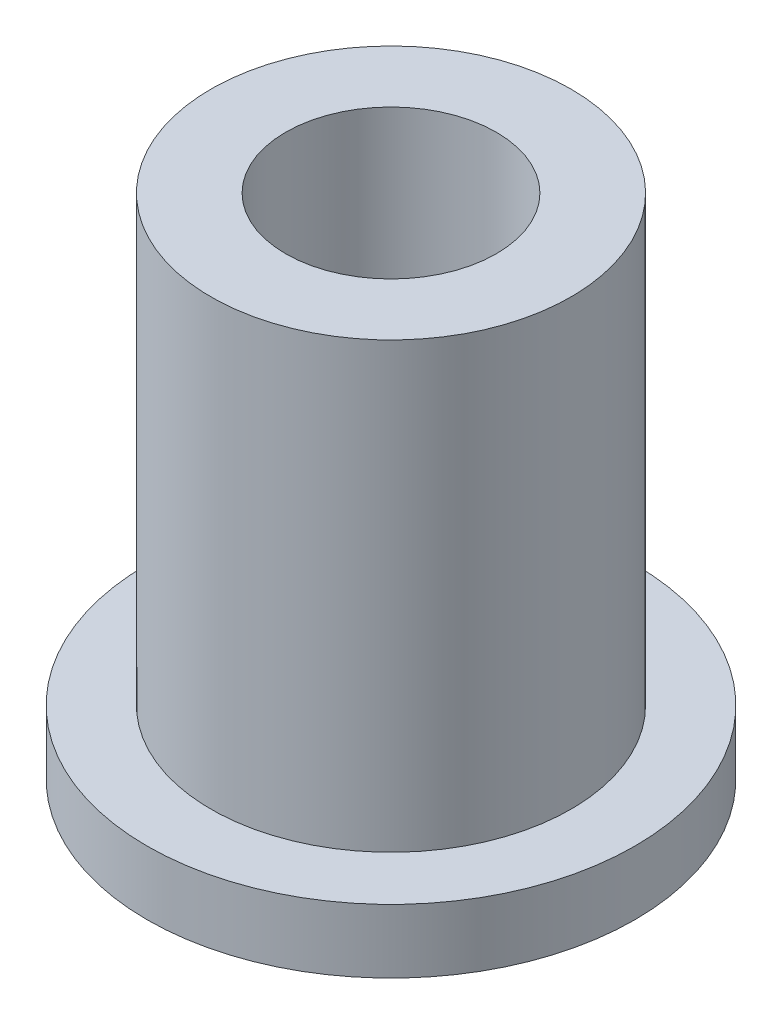
SolidWorks part; units mm, degrees
ref_plane "Front Plane" through (0, 0, 0) normal (0, 0, 1) x (1, 0, 0)
ref_plane "Top Plane" through (0, 0, 0) normal (0, 1, 0) x (1, 0, 0)
ref_plane "Right Plane" through (0, 0, 0) normal (1, 0, 0) x (0, 0, -1)
sketch "Sketch1" plane through (0, 0, 0) normal (1, 0, 0) x (0, 0, -1)
  line L0 (0, 0) -> (0, 8.4571) construction
  line L1 (0, 0) -> (3.82, 0)
  line L2 (3.82, 0) -> (3.82, 1)
  line L3 (3.82, 1) -> (2.82, 1)
  line L4 (2.82, 1) -> (2.82, 7.95)
  line L5 (2.82, 7.95) -> (0, 7.95)
  line L6 (0, 7.95) -> (0, 0)
  dimension "D1" = 7.95
  dimension "D2" = 5.64
  dimension "D3" = 1
  dimension "D4" = 1
revolve "Revolve1" add sketch "Sketch1" angle 360 about L0
hole_wizard "M4x0.7 Tapped Hole1" positions "3DSketch1" profile "Sketch2" tap size "M4x0.7" standard "ANSI Metric" end condition through all
sketch3d "3DSketch1"
  point P0 (0, 0, 0)
  point P3 (0, 0, 0)
sketch "Sketch2" plane through (0, 0, 0) normal (1, 0, 0) x (0, 0, -1)
  line L0 (0, 0) -> (0, 7.95)
  line L1 (0, 7.95) -> (1.65, 7.95)
  line L2 (1.65, 7.95) -> (1.65, 0)
  line L5 (1.65, 0) -> (0, 0)
  line L11 (0, -6.35) -> (0, 107.95) construction
  dimension "Thru Tap Drill Dia." = 3.3
  dimension "Thru Tap Drill Depth" = 7.95
cosmetic thread "Hole Thread3" parameters "D2"=4
cosmetic thread "Hole Thread4" parameters "D2"=4
